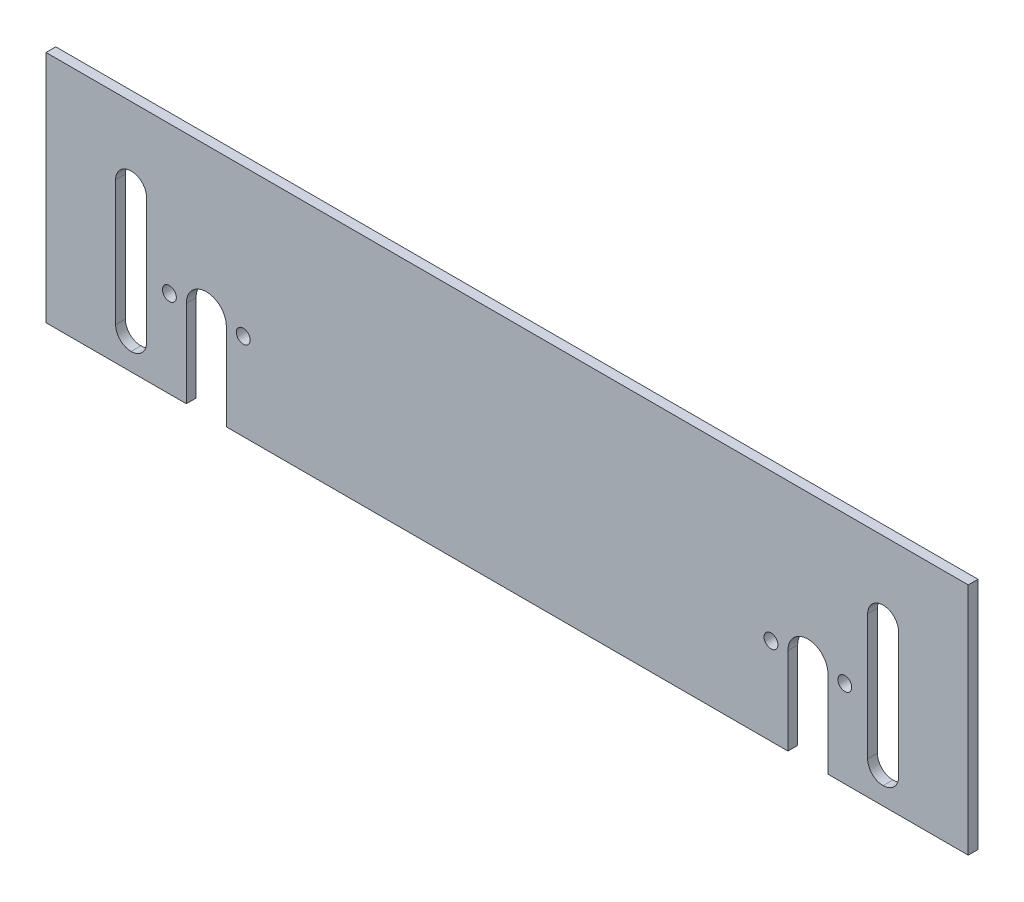
SolidWorks part; units mm, degrees
material "ABS"
ref_plane "X-Y Datum" through (0, 0, 0) normal (0, 0, 1) x (1, 0, 0)
ref_plane "X-Z Datum" through (0, 0, 0) normal (0, 1, 0) x (1, 0, 0)
ref_plane "Y-Z Datum" through (0, 0, 0) normal (1, 0, 0) x (0, 0, -1)
sketch "Sketch1" plane through (0, 0, 0) normal (0, 0, 1) x (1, 0, 0)
  line L1 (-149.85, 38.0375) -> (149.85, 38.0375)
  line L2 (-149.85, 38.0375) -> (-149.85, -38.0375)
  line L3 (-149.85, -38.0375) -> (149.85, -38.0375)
  line L4 (149.85, 38.0375) -> (149.85, -38.0375)
  line L5 (-149.85, 38.0375) -> (149.85, -38.0375) construction
  line L6 (-149.85, -38.0375) -> (149.85, 38.0375) construction
  point P0 (0, 0)
  dimension "D1" = 76.075
  dimension "D2" = 299.7
extrude "Boss-Extrude1" add sketch "Sketch1" along normal blind 3.175
sketch "Sketch3" plane through (0, 0, 0) normal (0, 0, -1) x (-1, 0, 0)
  line L3 (149.85, -38.0375) -> (-149.85, -38.0375) construction
  line L4 (149.85, -38.0375) -> (-149.85, -38.0375)
  line L5 (-104.25, -9.7625) -> (-104.25, -38.0375)
  line L6 (-91.25, -9.7625) -> (-91.25, -38.0375)
  line L7 (104.25, -9.7625) -> (104.25, -38.0375)
  line L8 (91.25, -9.7625) -> (91.25, -38.0375)
  circle A6 centre (-97.75, -9.7625) radius 6.5
  circle A7 centre (97.75, -9.7625) radius 6.5
  point P0 (97.75, -9.7625)
  point P1 (-97.75, -9.7625)
  point P16 (109.75, -9.7625)
  point P17 (85.75, -9.7625)
  point P18 (-85.75, -9.7625)
  point P19 (-109.75, -9.7625)
  dimension "D1" = 13
sketch "Sketch8" plane through (0, 0, 3.175) normal (0, 0, 1) x (1, 0, 0)
  line L1 (122.1609, 18.5125) -> (122.2247, 18.5125)
  line L4 (122.1928, -32.2824) -> (122.1928, 18.5125) construction
  line L5 (122.1609, -32.2824) -> (122.2247, -32.2824)
  line L6 (117.1609, -27.2824) -> (117.1609, 13.5125)
  line L8 (127.2247, -27.2824) -> (127.2247, 13.5125)
  line L9 (117.1609, -32.2824) -> (127.2247, 18.5125) construction
  line L10 (117.1609, 18.5125) -> (127.2247, -32.2824) construction
  arc A0 (122.1609, -32.2824) -> (117.1609, -27.2824) centre (122.1609, -27.2824) cw
  arc A1 (122.2247, -32.2824) -> (127.2247, -27.2824) centre (122.2247, -27.2824) ccw
  arc A2 (127.2247, 13.5125) -> (122.2247, 18.5125) centre (122.2247, 13.5125) ccw
  arc A3 (122.1609, 18.5125) -> (117.1609, 13.5125) centre (122.1609, 13.5125) ccw
  point P0 (122.1928, -6.885)
  dimension "D1" = 5
extrude "Cut-Extrude4" cut sketch "Sketch8" against normal through all
mirror "Mirror3" about plane through (0, 0, 0) normal (1, 0, 0) of "Cut-Extrude4"
extrude "Cut-Extrude5" cut sketch "Sketch3" against normal through all contours A6 | A6 L5 L4 L6 | A7 | A7 L8 L4 L7
hole_wizard "M4 Clearance Hole1" positions "Sketch11" profile "Sketch10" hole size "M4" standard "ANSI Metric" end condition through all
sketch "Sketch11" plane through (0, 0, 0) normal (0, 0, -1) x (-1, 0, 0)
  point P0 (-85.75, -9.7625)
  point P3 (-109.75, -9.7625)
  point P6 (109.75, -9.7625)
  point P9 (85.75, -9.7625)
sketch "Sketch10" plane through (85.75, -9.7625, 0) normal (1, 0, 0) x (0, 1, 0)
  line L0 (0, 0) -> (0, 3.175)
  line L1 (0, 3.175) -> (2.25, 3.175)
  line L2 (2.25, 3.175) -> (2.25, 0)
  line L5 (2.25, 0) -> (0, 0)
  line L11 (0, -6.35) -> (0, 107.95) construction
  dimension "Thru Hole Dia." = 4.5
  dimension "Thru Hole Depth" = 3.175
